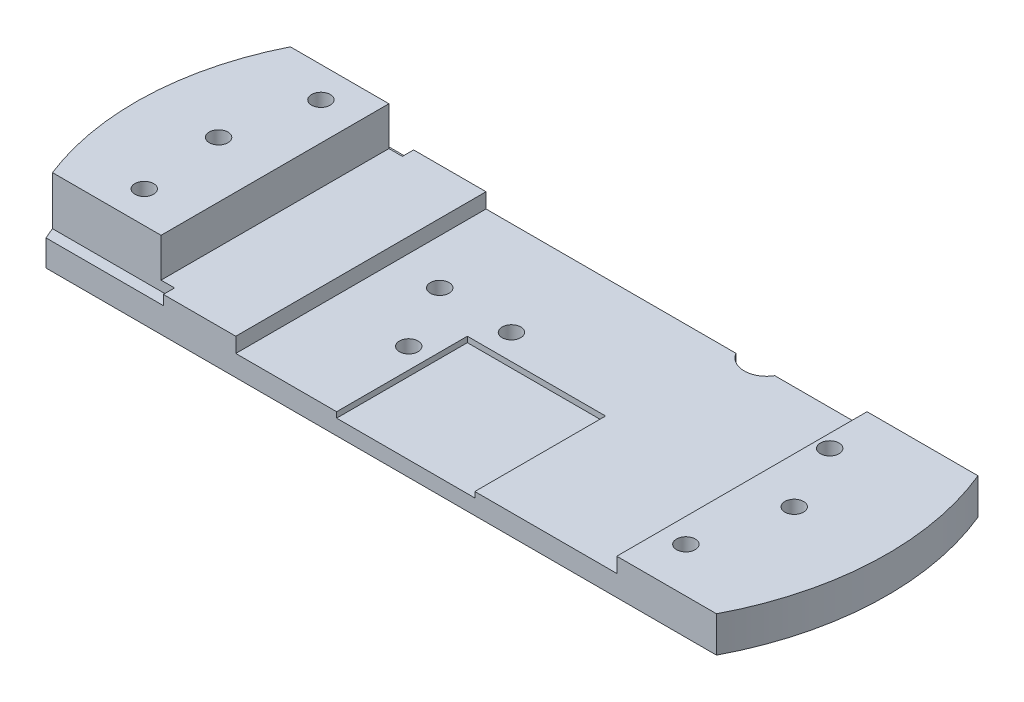
SolidWorks part; units mm, degrees
ref_plane "Front Plane" through (0, 0, 0) normal (0, 0, 1) x (1, 0, 0)
ref_plane "Top Plane" through (0, 0, 0) normal (0, 1, 0) x (1, 0, 0)
ref_plane "Right Plane" through (0, 0, 0) normal (1, 0, 0) x (0, 0, -1)
sketch "Sketch1" plane through (0, 0, 0) normal (0, 1, 0) x (1, 0, 0)
  line L1 (-97.5, -33.5) -> (97.5, -33.5)
  line L2 (-97.5, -33.5) -> (-97.5, 33.5)
  line L3 (-97.5, 33.5) -> (97.5, 33.5)
  line L4 (97.5, -33.5) -> (97.5, 33.5)
  line L5 (-97.5, -33.5) -> (97.5, 33.5) construction
  line L6 (-97.5, 33.5) -> (97.5, -33.5) construction
  point P0 (0, 0)
  dimension "D1" = 67
  dimension "D2" = 195
extrude "Boss-Extrude1" add sketch "Sketch1" along normal blind 20
sketch "Sketch2" plane through (0, 0, 0) normal (0, -1, 0) x (1, 0, 0)
  line L0 (-97.5, -33.5) -> (-97.5, 33.5) construction
  line L1 (97.5, 33.5) -> (97.5, -33.5) construction
  line L2 (97.5, 33.5) -> (88.5, 33.5)
  line L3 (-97.5, 33.5) -> (97.5, 33.5) construction
  line L4 (97.5, -33.5) -> (91.5, -33.5)
  line L5 (97.5, -33.5) -> (-97.5, -33.5) construction
  line L6 (-97.5, 33.5) -> (-91, 33.5)
  line L7 (-97.5, -33.5) -> (-88, -33.5)
  circle A0 centre (18.0922, -3.2198) radius 79.4078
  circle A1 centre (-22.6589, 2.9929) radius 74.8411
  line M7 (97.5, -33.5) -> (97.5, 33.5)
  line M8 (97.5, 33.5) -> (-97.5, 33.5)
  line M9 (-97.5, 33.5) -> (-97.5, -33.5)
  line M10 (-97.5, -33.5) -> (97.5, -33.5)
  dimension "D1" = 9
  dimension "D2" = 6
  dimension "D3" = 6.5
  dimension "D4" = 9.5
extrude "Cut-Extrude1" cut sketch "Sketch2" against normal blind 20 contours A0 M7 M8 | A0 M10 M7 | A1 M9 M10 | A1 M8 M9
sketch "Sketch3" plane through (0, 0, 33.5) normal (0, 0, -1) x (-1, 0, 0)
  line L0 (97.5, 20) -> (63.2, 20)
  line L1 (-91.5, 20) -> (88, 20) construction
  line L2 (63.2, 20) -> (63.2, 9.6)
  line L3 (63.2, 9.6) -> (40.2, 9.6)
  line L4 (40.2, 9.6) -> (40.2, 5.6)
  line L5 (40.2, 5.6) -> (-61.8, 5.6)
  line L7 (91, 20) -> (-88.5, 20) construction
  line L10 (97.5, 0) -> (97.5, 20) construction
  line L11 (-61.8, 5.6) -> (-61.8, 9.6)
  line L12 (-61.8, 9.6) -> (-97.5, 9.6)
  line L13 (-97.5, 20) -> (-97.5, 0) construction
  line L14 (-97.5, 9.6) -> (-97.5, 20)
  line L15 (-97.5, 20) -> (63.2, 20)
  line M13 (-88.5, 0) -> (-88.5, 20)
  line M14 (-88.5, 20) -> (91, 20)
  dimension "D1" = 10.4
  dimension "D2" = 34.3
  dimension "D3" = 23
  dimension "D4" = 4
  dimension "D5" = 102
extrude "Cut-Extrude2" cut sketch "Sketch3" along normal through all contours L11 L12 L2 L3 L4 L5 M13 M14
sketch "Sketch4" plane through (0, 20, 0) normal (0, 1, 0) x (1, 0, 0)
  line L0 (-59.5873, 33.5) -> (-59.5873, 30.5)
  line L1 (-63.2, 33.5) -> (-88, 33.5) construction
  line L2 (-59.5873, 30.5) -> (-89.5873, 30.5)
  line L3 (-59.5873, -33.5) -> (-59.5873, -30.5)
  line L4 (-91, -33.5) -> (-63.2, -33.5) construction
  line L5 (-59.5873, -30.5) -> (-92.2617, -30.5)
  line L6 (-59.5873, 33.5) -> (-63.2, 33.5)
  line L7 (-59.5873, -33.5) -> (-63.2, -33.5)
  arc A0 (-88, 33.5) -> (-91, -33.5) centre (-22.6589, -2.9929) ccw construction
  line M5 (-91, -33.5) -> (-63.2, -33.5)
  line M6 (-63.2, -33.5) -> (-63.2, 33.5)
  line M7 (-63.2, 33.5) -> (-88, 33.5)
  arc M8 (-88, 33.5) -> (-91, -33.5) centre (-22.6589, -2.9929) ccw
  dimension "D1" = 3
  dimension "D2" = 3
  dimension "D3" = 30
extrude "Cut-Extrude3" cut sketch "Sketch4" against normal blind 13 contours L2 M6 M7 M8 | L0 L6 L2 M6 | L5 M6 M8 M5 | L7 L3 L5 M6
sketch "Sketch6" plane through (0, 0, 0) normal (0, -1, 0) x (1, 0, 0)
  line L0 (-63.2, -33.5) -> (-97.5, -33.5)
  line L1 (91.5, -33.5) -> (-88, -33.5) construction
  line L2 (-63.2, -33.5) -> (-63.2, 33.5)
  line L3 (-91, 33.5) -> (88.5, 33.5) construction
  line L4 (-63.2, -9) -> (-28.1, -9) construction
  line L5 (-63.2, 8.7) -> (-18.7, 8.7) construction
  line L6 (-63.2, -8.3) -> (-8.2, -8.3) construction
  line L8 (91.5, -33.5) -> (-88, -33.5) construction
  line L9 (-97.5, -33.5) -> (-97.5, 33.5)
  line L10 (-97.5, 33.5) -> (-63.2, 33.5)
  circle A0 centre (-28.1, -9) radius 2.5
  circle A1 centre (-18.7, 8.7) radius 2.5
  circle A2 centre (74.1, -1.7) radius 2.5
  circle A3 centre (68.3, 21.5) radius 2.5
  circle A4 centre (65.3, -20) radius 2.5
  circle A5 centre (-8.2, -8.3) radius 2.5
  circle A6 centre (-76.2, 22) radius 2.5
  circle A7 centre (-78.2, 0.1) radius 2.5
  circle A8 centre (-73.2, -22.3) radius 2.5
  arc A10 (-91, 33.5) -> (-88, -33.5) centre (-22.6589, 2.9929) ccw construction
  dimension "D2" = 5
  dimension "D3" = 35.1
  dimension "D4" = 34.3
  dimension "D5" = 44.5
  dimension "D6" = 24.5
  dimension "D7" = 55
  dimension "D8" = 42.2
  dimension "D9" = 137.3
  dimension "D10" = 128.5
  dimension "D11" = 131.5
  dimension "D12" = 10
  dimension "D13" = 15
  dimension "D14" = 13
  dimension "D15" = 11.2
  dimension "D16" = 33.6
  dimension "D17" = 55.5
  dimension "D18" = 31.8
  dimension "D19" = 55
  dimension "D20" = 13.5
  dimension "D21" = 25.2
extrude "Cut-Extrude4" cut sketch "Sketch6" against normal through all contours A0 | A5 | A1 | A6 | A7 | A8 | A4 | A2 | A3
sketch "Sketch7" plane through (0, 5.6, 0) normal (0, 1, 0) x (1, 0, 0)
  line L1 (-13.2, 1.5) -> (23.8, 1.5)
  line L2 (-13.2, 1.5) -> (-13.2, -33.5)
  line L3 (-13.2, -33.5) -> (23.8, -33.5)
  line L4 (23.8, 1.5) -> (23.8, -33.5)
  line L8 (-63.2, 30.5) -> (-63.2, -30.5) construction
  line L9 (-63.2, 30.5) -> (-63.2, -30.5) construction
  line L10 (-40.2, -33.5) -> (61.8, -33.5) construction
  dimension "D1" = 50
  dimension "D2" = 87
  dimension "D3" = 35
extrude "Cut-Extrude5" cut sketch "Sketch7" against normal blind 1.5
sketch "Sketch8" plane through (0, 20, 0) normal (0, 1, 0) x (1, 0, 0)
  line L0 (-59.5873, -33.5) -> (-97.5, -33.5)
  line L1 (-97.5, -33.5) -> (-97.5, 33.5)
  line L3 (-97.5, 33.5) -> (31.9, 33.5)
  line L6 (31.9, 36.5) -> (31.9, 30.5)
  line L7 (31.9, 33.5) -> (37.0962, 33.5)
  line L10 (-59.5873, 33.5) -> (-88, 33.5) construction
  line L11 (-40.2, 33.5) -> (61.8, 33.5) construction
  circle A1 centre (31.9, 36.5) radius 6
  arc A2 (-89.5873, 30.5) -> (-92.2617, -30.5) centre (-22.6589, -2.9929) ccw construction
  dimension "D1" = 12
  dimension "D2" = 129.4
extrude "Cut-Extrude6" cut sketch "Sketch8" against normal blind 18.5 contours L6 A1 L7 | L3 A1 L6
